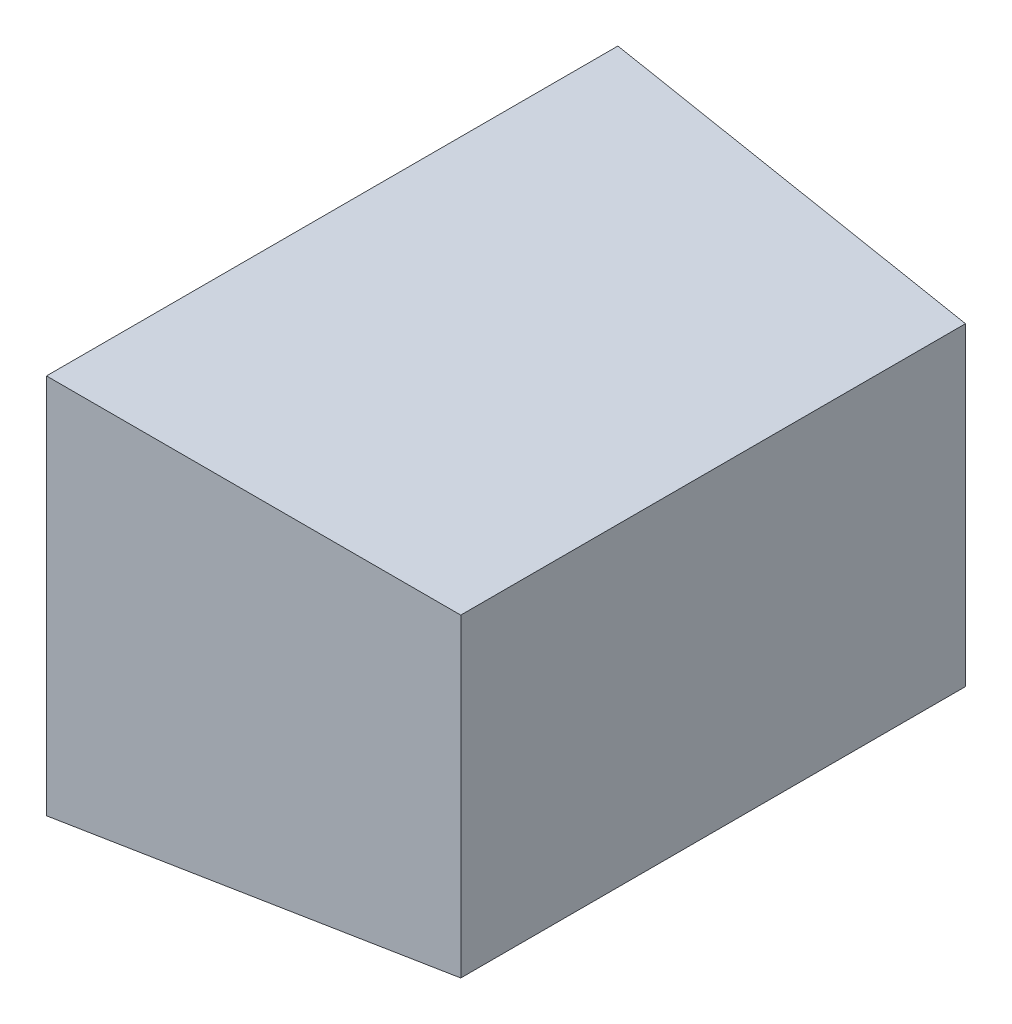
SolidWorks part; units mm, degrees
ref_plane "Front Plane" through (0, 0, 0) normal (0, 0, 1) x (1, 0, 0)
ref_plane "Top Plane" through (0, 0, 0) normal (0, 1, 0) x (1, 0, 0)
ref_plane "Right Plane" through (0, 0, 0) normal (1, 0, 0) x (0, 0, -1)
sketch "Sketch2" plane through (0, 0, 0) normal (1, 0, 0) x (0, 0, -1)
  line L1 (-75, 50) -> (75, 50)
  line L2 (-75, 50) -> (-75, -50)
  line L3 (-75, -50) -> (75, -50)
  line L4 (75, 50) -> (75, -50)
  line L5 (-75, 50) -> (75, -50) construction
  line L6 (-75, -50) -> (75, 50) construction
  point P0 (0, 0)
  dimension "D1" = 150
  dimension "D2" = 100
extrude "Boss-Extrude1" add sketch "Sketch2" along normal blind 100 draft 5
